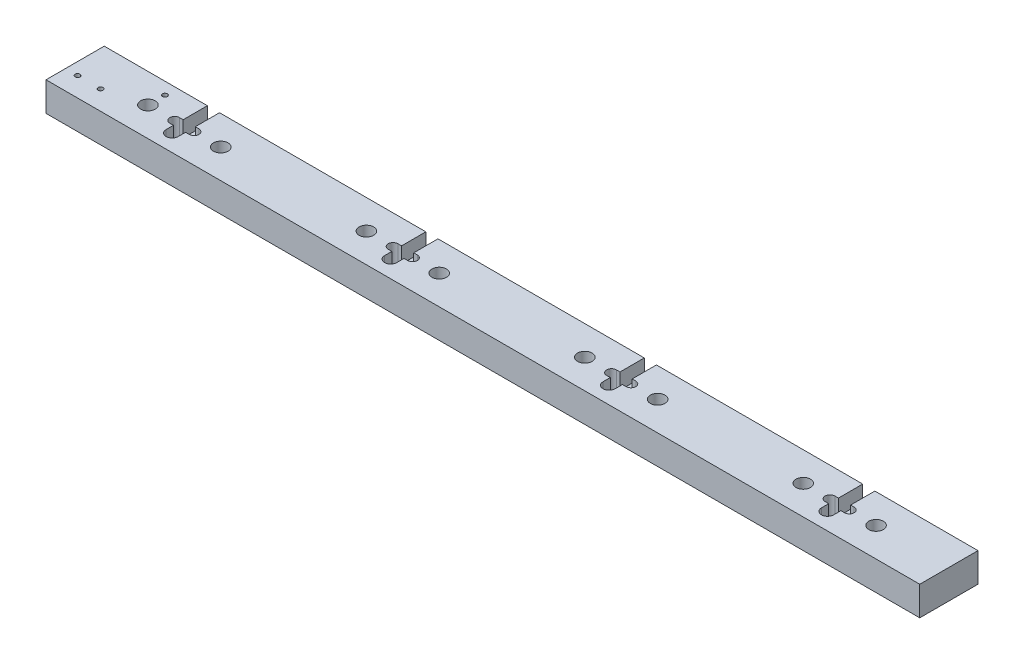
SolidWorks part; units mm, degrees
material "HDPE-green"
ref_plane "Front Plane" through (0, 0, 0) normal (0, 0, 1) x (1, 0, 0)
ref_plane "Top Plane" through (0, 0, 0) normal (0, 1, 0) x (1, 0, 0)
ref_plane "Right Plane" through (0, 0, 0) normal (1, 0, 0) x (0, 0, -1)
sketch "Sketch1" plane through (0, 0, 0) normal (0, 1, 0) x (1, 0, 0)
  line L1 (-180, -12) -> (180, -12)
  line L2 (-180, -12) -> (-180, 12)
  line L3 (-180, 12) -> (180, 12)
  line L4 (180, -12) -> (180, 12)
  line L5 (-180, -12) -> (180, 12) construction
  line L6 (-180, 12) -> (180, -12) construction
  point P0 (0, 0)
  dimension "D1" = 24
  dimension "D2" = 360
extrude "Boss-Extrude1" add sketch "Sketch1" along normal blind 12
sketch "Sketch2" plane through (0, 12, 0) normal (0, 1, 0) x (1, 0, 0)
  line L0 (-180, 12) -> (-180, -12) construction
  circle A0 centre (-150, 0) radius 3
  circle A1 centre (-120, 0) radius 3
  dimension "D1" = 6
  dimension "D3" = 6
  dimension "D2" = 30
  dimension "D4" = 60
extrude "Cut-Extrude1" cut sketch "Sketch2" against normal up to next
sketch "Sketch11" plane through (-63.4848, 12, 93.4814) normal (0, 1, 0) x (-1, 0, 0)
  line L0 (67.5152, -93.4814) -> (75.5152, -93.4814) construction
  line L1 (67.5152, -91.4814) -> (75.5152, -91.4814)
  line L2 (67.5152, -95.4814) -> (75.5152, -95.4814)
  line L3 (-243.4848, -105.4814) -> (116.5152, -105.4814) construction
  arc A0 (67.5152, -91.4814) -> (67.5152, -95.4814) centre (67.5152, -93.4814) ccw
  arc A1 (75.5152, -95.4814) -> (75.5152, -91.4814) centre (75.5152, -93.4814) ccw
  point P2 (71.5152, -93.4814)
  dimension "D1" = 8
  dimension "D2" = 2
  dimension "D4" = 135
  dimension "D3" = 12
extrude "Cut-Extrude2" cut sketch "Sketch11" against normal blind 8
sketch "Sketch13" plane through (-63.4848, 12, 93.4814) normal (0, 1, 0) x (-1, 0, 0)
  line L0 (71.5152, -88.4814) -> (71.5152, -142.1112) construction
  line L1 (74.0152, -88.4814) -> (74.0152, -142.1112)
  line L2 (69.0152, -88.4814) -> (69.0152, -142.1112)
  line L3 (-243.4848, -105.4814) -> (116.5152, -105.4814) construction
  arc A0 (74.0152, -88.4814) -> (69.0152, -88.4814) centre (71.5152, -88.4814) ccw
  arc A1 (69.0152, -142.1112) -> (74.0152, -142.1112) centre (71.5152, -142.1112) ccw
  point P2 (71.5152, -115.2963)
  dimension "D1" = 17
  dimension "D2" = 2.5
  dimension "D3" = 135
extrude "Cut-Extrude3" cut sketch "Sketch13" against normal blind 6.5
pattern_linear "LPattern1" count 4 spacing 90 along (1, 0, 0) of "Cut-Extrude1", "Cut-Extrude2", "Cut-Extrude3"
hole_wizard "Ø2.0 (2) Diameter Hole1" positions "Sketch5" profile "Sketch4" hole size "Ø2.0" standard "ISO" end condition up to next
sketch "Sketch5" plane through (0, 0, 0) normal (0, -1, 0) x (1, 0, 0)
  line L0 (-180, 12) -> (180, 12) construction
  line L1 (-180, -12) -> (-180, 12) construction
  line L2 (-180, -12) -> (-180, 12) construction
  line L3 (-180, 12) -> (180, 12) construction
  point P0 (-175, 4)
  point P1 (-165.5, 4)
  point P9 (-150, -7)
  dimension "D1" = 8
  dimension "D2" = 8
  dimension "D3" = 5
  dimension "D4" = 9.5
  dimension "D5" = 30
  dimension "D6" = 19
sketch "Sketch4" plane through (-175, 0, 4) normal (1, 0, 0) x (0, 0, -1)
  line L0 (0, 0) -> (0, 12)
  line L1 (0, 12) -> (1, 12)
  line L2 (1, 12) -> (1, 0)
  line L5 (1, 0) -> (0, 0)
  line L11 (0, -6.35) -> (0, 107.95) construction
  dimension "Thru Hole Dia." = 2
  dimension "Thru Hole Depth" = 12
